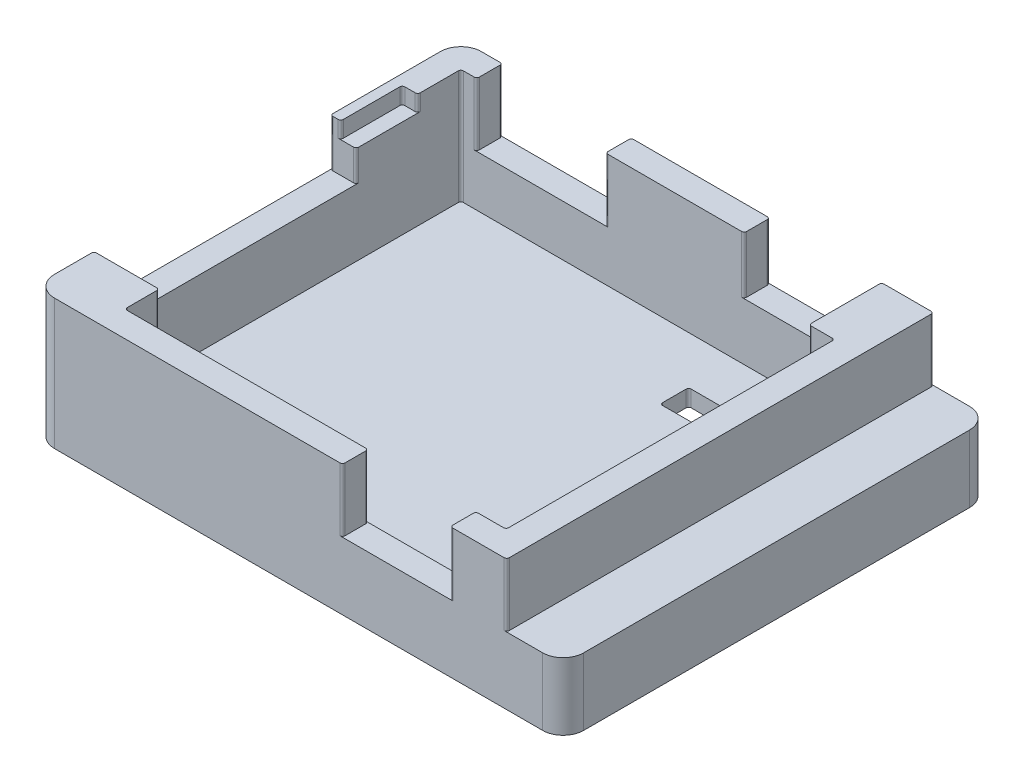
SolidWorks part; units mm, degrees
ref_plane "Front Plane" through (0, 0, 0) normal (0, 0, 1) x (1, 0, 0)
ref_plane "Top Plane" through (0, 0, 0) normal (0, 1, 0) x (1, 0, 0)
ref_plane "Right Plane" through (0, 0, 0) normal (1, 0, 0) x (0, 0, -1)
sketch "Sketch1" plane through (0, 0, 0) normal (0, 1, 0) x (1, 0, 0)
  line L1 (0, 0) -> (103.124, 0)
  line L2 (0, 0) -> (0, 83.185)
  line L3 (0, 83.185) -> (103.124, 83.185)
  line L4 (103.124, 0) -> (103.124, 83.185)
  dimension "D1" = 103.124
  dimension "D2" = 83.185
extrude "Boss-Extrude1" add sketch "Sketch1" along normal blind 25.4
sketch "Sketch2" plane through (0, 25.4, 0) normal (0, 1, 0) x (1, 0, 0)
  line L0 (0, 83.185) -> (0, 0) construction
  line L1 (5, 78.185) -> (82, 78.185)
  line L2 (5, 78.185) -> (5, 11.7)
  line L3 (12.7, 5) -> (87, 5)
  line L4 (87, 69.0118) -> (87, 5)
  line L5 (103.124, 83.185) -> (0, 83.185) construction
  line L6 (0, 0) -> (103.124, 0) construction
  line L7 (5, 11.7) -> (12.7, 11.7)
  line L8 (12.7, 11.7) -> (12.7, 5)
  line L9 (82, 78.185) -> (82, 69.0118)
  line L10 (82, 69.0118) -> (87, 69.0118)
  dimension "D1" = 5
  dimension "D2" = 5
  dimension "D3" = 82
  dimension "D4" = 5
  dimension "D5" = 11.7
  dimension "D6" = 12.7
  dimension "D7" = 77
  dimension "D8" = 14.1732
extrude "Cut-Extrude1" cut sketch "Sketch2" against normal offset from surface (22.225 mm away) 3.175 from surface at 0 up to face at (51.562, 0, -41.5925) starting at face at (51.562, 25.4, -41.5925)
sketch "Sketch3" plane through (0, 25.4, 0) normal (0, 1, 0) x (1, 0, 0)
  line L0 (0, 0) -> (103.124, 0) construction
  line L1 (103.124, 83.185) -> (92.124, 83.185)
  line L2 (103.124, 83.185) -> (103.124, 0)
  line L3 (103.124, 0) -> (92.124, 0)
  line L4 (92.124, 83.185) -> (92.124, 0)
  dimension "D1" = 11
extrude "Cut-Extrude2" cut sketch "Sketch3" against normal blind 12.3
sketch "Sketch4" plane through (0, 0, -83.185) normal (0, 0, -1) x (-1, 0, 0)
  line L0 (-92.124, 25.4) -> (0, 25.4) construction
  line L1 (-82, 25.4) -> (-60.2, 25.4)
  line L2 (-82, 25.4) -> (-82, 14.3)
  line L3 (-82, 14.3) -> (-60.2, 14.3)
  line L4 (-60.2, 25.4) -> (-60.2, 14.3)
  line L6 (0, 25.4) -> (0, 0) construction
  line L7 (-33.2, 25.4) -> (-8.1, 25.4)
  line L8 (-33.2, 25.4) -> (-33.2, 13.1)
  line L9 (-33.2, 13.1) -> (-8.1, 13.1)
  line L10 (-8.1, 25.4) -> (-8.1, 13.1)
  line L11 (-82, 3.175) -> (-82, 25.4) construction
  line L12 (-92.124, 13.1) -> (-92.124, 25.4) construction
  dimension "D1" = 10.124
  dimension "D2" = 21.8
  dimension "D3" = 11.1
  dimension "D4" = 12.3
  dimension "D5" = 27
  dimension "D6" = 8.1
  dimension "D7" = 25.1
extrude "Cut-Extrude3" cut sketch "Sketch4" against normal up to next
sketch "Sketch6" plane through (0, 0, 0) normal (-1, 0, 0) x (0, 0, 1)
  line L0 (-83.185, 25.4) -> (0, 25.4) construction
  line L1 (-11.7, 25.4) -> (-57.785, 25.4)
  line L2 (-11.7, 25.4) -> (-11.7, 16.2)
  line L3 (-11.7, 16.2) -> (-57.785, 16.2)
  line L4 (-57.785, 25.4) -> (-57.785, 16.2)
  line L5 (-83.185, 25.4) -> (-83.185, 0) construction
  line L6 (-11.7, 3.175) -> (-11.7, 25.4) construction
  dimension "D1" = 46.085
  dimension "D2" = 9.2
  dimension "D3" = 25.4
extrude "Cut-Extrude5" cut sketch "Sketch6" against normal blind 5.08
sketch "Sketch7" plane through (0, 25.4, 0) normal (0, 1, 0) x (1, 0, 0)
  line L0 (0, 83.185) -> (0, 57.785) construction
  line L1 (5, 57.785) -> (2, 57.785)
  line L2 (5, 57.785) -> (5, 69.785)
  line L3 (5, 69.785) -> (2, 69.785)
  line L4 (2, 57.785) -> (2, 69.785)
  dimension "D1" = 12
  dimension "D2" = 2
extrude "Cut-Extrude6" cut sketch "Sketch7" against normal blind 3.175
sketch "Sketch8" plane through (0, 0, 0) normal (0, -1, 0) x (1, 0, 0)
  line L1 (58.674, -63.3413) -> (69.7865, -63.3413)
  line L2 (58.674, -63.3413) -> (58.674, -68.8975)
  line L3 (58.674, -68.8975) -> (69.7865, -68.8975)
  line L4 (69.7865, -63.3413) -> (69.7865, -68.8975)
  line L6 (103.124, -83.185) -> (0, -83.185) construction
  line L8 (103.124, 0) -> (103.124, -83.185) construction
  dimension "D1" = 33.3375
  dimension "D2" = 5.5562
  dimension "D3" = 14.2875
  dimension "D4" = 11.1125
extrude "Cut-Extrude7" cut sketch "Sketch8" against normal blind 5.08
fillet "Fillet1" radius 4 4 edges at (103.124, 6.55, -83.185) (103.124, 6.55, 0) (0, 12.7, 0) (0, 12.7, -83.185)
sketch "Sketch9" plane through (0, 0, 0) normal (0, 0, 1) x (1, 0, 0)
  line L0 (4, 25.4) -> (92.124, 25.4) construction
  line L1 (81.124, 25.4) -> (60.124, 25.4)
  line L2 (81.124, 25.4) -> (81.124, 13.1)
  line L3 (81.124, 13.1) -> (60.124, 13.1)
  line L4 (60.124, 25.4) -> (60.124, 13.1)
  line L5 (92.124, 13.1) -> (92.124, 25.4) construction
  dimension "D1" = 11
  dimension "D2" = 21
  dimension "D3" = 12.3
extrude "Cut-Extrude8" cut sketch "Sketch9" against normal up to next
fillet "Fillet2" radius 0.5 31 edges at (5, 9.6875, -11.7) (0, 20.8, -11.7) (12.7, 14.2875, -11.7) (12.7, 14.2875, -5) (60.124, 19.25, -5) (60.124, 19.25, 0) (92.124, 19.25, 0) (81.124, 19.25, 0) (81.124, 19.25, -5) (87, 14.2875, -5) (87, 14.2875, -69.0118) (82, 14.2875, -69.0118) (82, 19.85, -83.185) (92.124, 19.25, -83.185) (60.2, 19.85, -83.185) (60.2, 19.85, -78.185) (33.2, 19.25, -78.185) (33.2, 19.25, -83.185) (8.1, 19.25, -83.185) (8.1, 19.25, -78.185) (5, 14.2875, -78.185) (5, 23.8125, -69.785) (2, 23.8125, -69.785) (5, 19.2125, -57.785) (2, 23.8125, -57.785) (0, 20.8, -57.785) (58.674, 1.5875, -68.8975) (82, 8.7375, -78.185) (69.7865, 1.5875, -68.8975) (69.7865, 1.5875, -63.3413) (58.674, 1.5875, -63.3413)
